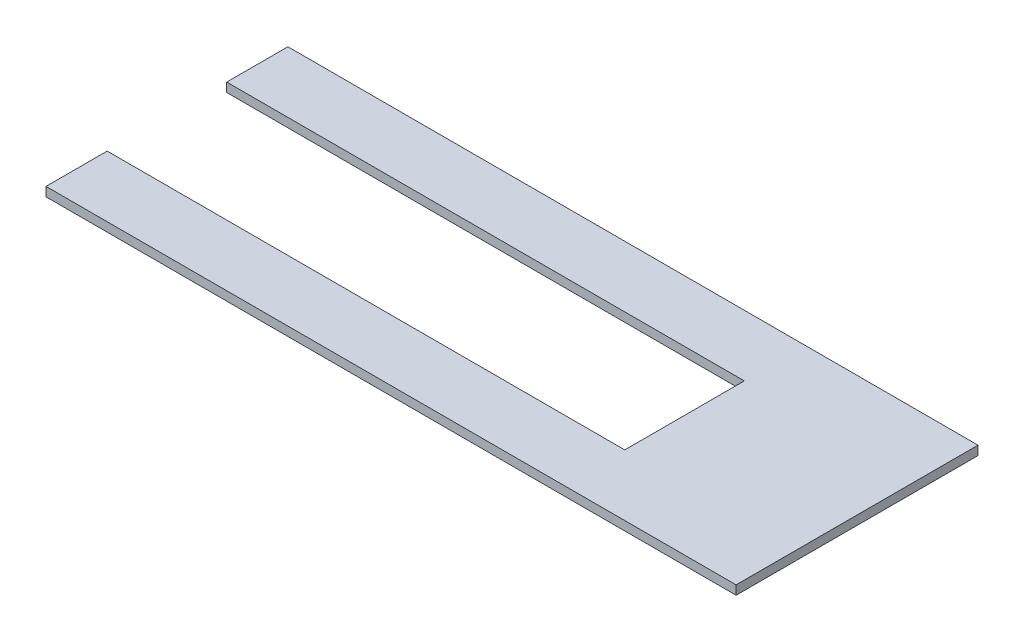
SolidWorks part; units mm, degrees
ref_plane "Front Plane" through (0, 0, 0) normal (0, 0, 1) x (1, 0, 0)
ref_plane "Top Plane" through (0, 0, 0) normal (0, 1, 0) x (1, 0, 0)
ref_plane "Right Plane" through (0, 0, 0) normal (1, 0, 0) x (0, 0, -1)
sketch "Sketch1" plane through (0, 0, 0) normal (0, 1, 0) x (1, 0, 0)
  line L0 (-485.3068, 168) -> (484.6932, 168)
  line L1 (484.6932, 168) -> (484.6932, -172)
  line L2 (484.6932, -172) -> (-485.3068, -172)
  line L3 (-485, 0) -> (-0.3068, -172) construction
  line L4 (0, -4) -> (-485.3068, -172) construction
  line L5 (-242.6534, -86) -> (-485.3068, -86) construction
  line L6 (0, -4) -> (484.6932, -172) construction
  line L7 (-485.3068, -86) -> (484.6932, -86) construction
  line L8 (-485.3068, 168) -> (0, -4) construction
  line L9 (-0.3068, 168) -> (-485, 0) construction
  line L10 (-242.6534, 82) -> (-485.3068, 82) construction
  line L11 (0, -4) -> (484.6932, 168) construction
  line L12 (-242.6534, 82) -> (484.6932, 82) construction
  line L13 (-485.3068, 168) -> (-485.3068, 82)
  line L14 (-0.3068, 168) -> (484.6932, 82) construction
  line L15 (484.6932, 168) -> (0, 82) construction
  line L17 (242.1932, 125) -> (242.1932, -86) construction
  line L18 (-485.3068, 82) -> (242.1932, 82) construction
  line L19 (242.1932, 82) -> (242.1932, -86) construction
  line L20 (-485.3068, 82) -> (242.1932, 82)
  line L21 (242.1932, 82) -> (242.1932, -86)
  line L22 (242.1932, -86) -> (-485.3068, -86)
  line L23 (-485.3068, -86) -> (-485.3068, -172)
  dimension "D1" = 86
  dimension "D2" = 970
  dimension "D3" = 340
  dimension "D4" = 485
extrude "Boss-Extrude1" add sketch "Sketch1" along normal blind 12.7 contours L22 L23 L2 L1 L0 L13 L20 L21
